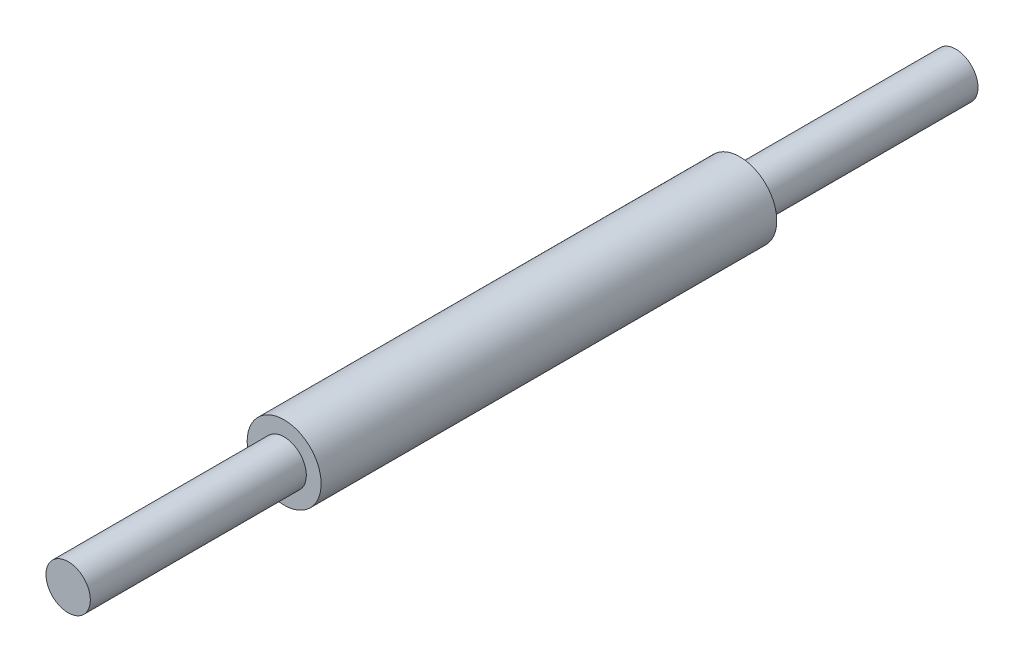
SolidWorks part; units mm, degrees
ref_plane "Front Plane" through (0, 0, 0) normal (0, 0, 1) x (1, 0, 0)
ref_plane "Top Plane" through (0, 0, 0) normal (0, 1, 0) x (1, 0, 0)
ref_plane "Right Plane" through (0, 0, 0) normal (1, 0, 0) x (0, 0, -1)
sketch "Sketch1" plane through (0, 0, 0) normal (0, 0, 1) x (1, 0, 0)
  circle A0 centre (0, 0) radius 2.5
  dimension "D1" = 5
extrude "Boss-Extrude1" add sketch "Sketch1" along normal mid plane 30.8
sketch "Sketch2" plane through (0, 0, 0) normal (0, 0, 1) x (1, 0, 0)
  circle A0 centre (0, 0) radius 1.5
  dimension "D1" = 3
extrude "Boss-Extrude2" add sketch "Sketch2" along normal mid plane 60
